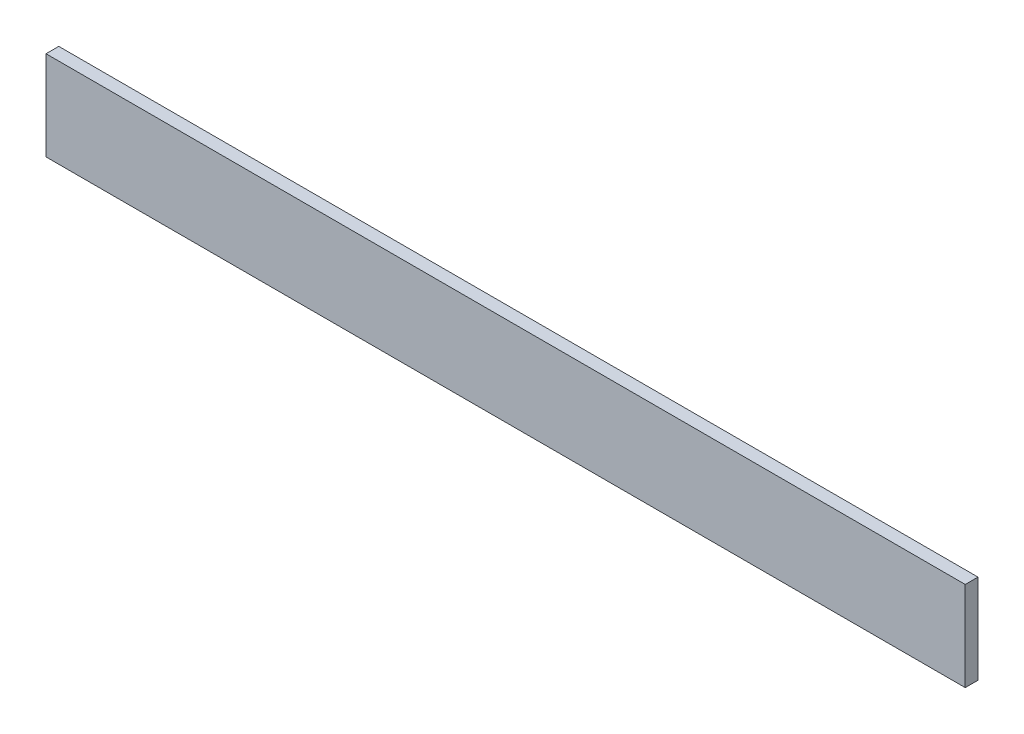
SolidWorks part; units mm, degrees
ref_plane "Front Plane" through (0, 0, 0) normal (0, 0, 1) x (1, 0, 0)
ref_plane "Top Plane" through (0, 0, 0) normal (0, 1, 0) x (1, 0, 0)
ref_plane "Right Plane" through (0, 0, 0) normal (1, 0, 0) x (0, 0, -1)
sketch "Sketch1" plane through (0, 0, 0) normal (0, 0, 1) x (1, 0, 0)
  line L1 (0, 0) -> (180, 0)
  line L2 (0, 0) -> (0, 17.5)
  line L3 (0, 17.5) -> (180, 17.5)
  line L4 (180, 0) -> (180, 17.5)
  dimension "D1" = 180
  dimension "D2" = 17.5
extrude "Boss-Extrude1" add sketch "Sketch1" along normal blind 2.5
